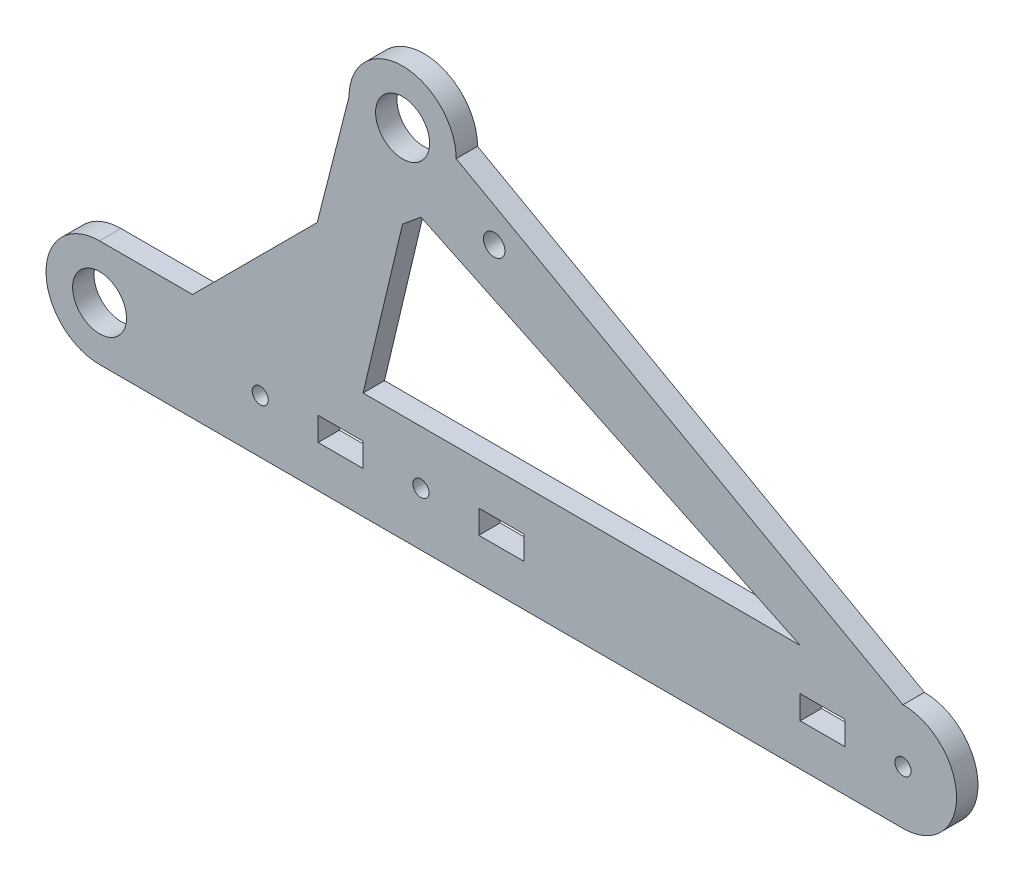
SolidWorks part; units mm, degrees
ref_plane "前视基准面" through (0, 0, 0) normal (0, 0, 1) x (1, 0, 0)
ref_plane "上视基准面" through (0, 0, 0) normal (0, 1, 0) x (1, 0, 0)
ref_plane "右视基准面" through (0, 0, 0) normal (1, 0, 0) x (0, 0, -1)
sketch "草图1" plane through (0, 0, 0) normal (0, 0, 1) x (1, 0, 0)
  line L0 (60, 0) -> (60, 0.846) construction
  line L1 (0, 0) -> (56.5685, 56.5685) construction
  line L6 (0, 0) -> (150, 0) construction
  line L7 (70.8, 2.2) -> (70.8, -2.2)
  line L13 (40.8, 2.2) -> (49.2, 2.2)
  line L14 (40.8, 2.2) -> (40.8, -2.2)
  line L23 (40.8, -2.2) -> (49.2, -2.2)
  line L32 (49.2, 2.2) -> (49.2, -2.2)
  line L33 (40.8, 2.2) -> (49.2, -2.2) construction
  line L34 (40.8, -2.2) -> (49.2, 2.2) construction
  line L35 (79.2, -2.2) -> (70.8, -2.2)
  line L36 (79.2, 2.2) -> (79.2, -2.2)
  line L37 (79.2, 2.2) -> (70.8, 2.2)
  line L38 (56.5685, 56.5685) -> (150, 0) construction
  line L54 (150, 0) -> (135, 0) construction
  line L55 (30, 0) -> (56.5685, 56.5685) construction
  line L56 (130.8, 2.2) -> (139.2, 2.2)
  line L57 (130.8, 2.2) -> (130.8, -2.2)
  line L58 (130.8, -2.2) -> (139.2, -2.2)
  line L59 (139.2, 2.2) -> (139.2, -2.2)
  line L60 (130.8, 2.2) -> (139.2, -2.2) construction
  line L61 (130.8, -2.2) -> (139.2, 2.2) construction
  line L62 (0, 10) -> (34.6967, 10)
  line L63 (0, -10) -> (150, -10)
  line L64 (66.5688, 56.5685) -> (150, 10)
  line L65 (34.6967, 10) -> (46.5683, 56.5685)
  line L66 (56.5685, 40.9926) -> (49.2, 10)
  line L67 (49.2, 10) -> (130.8, 10)
  line L68 (130.8, 10) -> (60, 43.8442)
  line L69 (60, 43.8442) -> (56.5685, 40.9926)
  circle A0 centre (0, 0) radius 5.03
  circle A1 centre (56.5685, 56.5685) radius 5.04
  circle A6 centre (30, 0) radius 1.5
  circle A21 centre (60, 0) radius 1.5
  circle A23 centre (150, 0) radius 1.5
  circle A24 centre (0, 0) radius 10 construction
  arc A25 (0, 10) -> (0, -10) centre (0, 0) ccw
  circle A26 centre (150, 0) radius 10 construction
  circle A27 centre (56.5685, 56.5685) radius 10.0002 construction
  arc A28 (46.5683, 56.5685) -> (66.5688, 56.5685) centre (56.5685, 56.5685) cw
  arc A29 (150, 10) -> (150, -10) centre (150, 0) cw
  circle A30 centre (73.6771, 46.2101) radius 2
  point P10 (45, 0)
  point P38 (7.7942, 4.5)
  point P45 (7.7942, -4.5)
  point P48 (0, 9)
  point P51 (48.7743, 52.0685)
  dimension "D1" = 3
  dimension "D2" = 10.08
  dimension "D3" = 30
  dimension "D4" = 15
  dimension "D5" = 8.4
  dimension "D7" = 80
  dimension "D9" = 90
  dimension "D10" = 8.4
  dimension "D12" = 10.06
  dimension "D13" = 4.4
  dimension "D8" = 20
  dimension "D6" = 4.4
  dimension "D14" = 45
extrude "凸台-拉伸1" add sketch "草图1" along normal blind 4
sketch "草图2" plane through (0, 0, 4) normal (0, 0, 1) x (1, 0, 0)
  line L0 (34.6967, 10) -> (40.6325, 33.2843)
  line L1 (46.5683, 56.5685) -> (34.6967, 10) construction
  line L2 (40.6325, 33.2843) -> (17.3483, 10)
  line L3 (34.6967, 10) -> (0, 10) construction
  line L4 (17.3483, 10) -> (34.6967, 10)
extrude "凸台-拉伸2" add sketch "草图2" against normal blind 4
